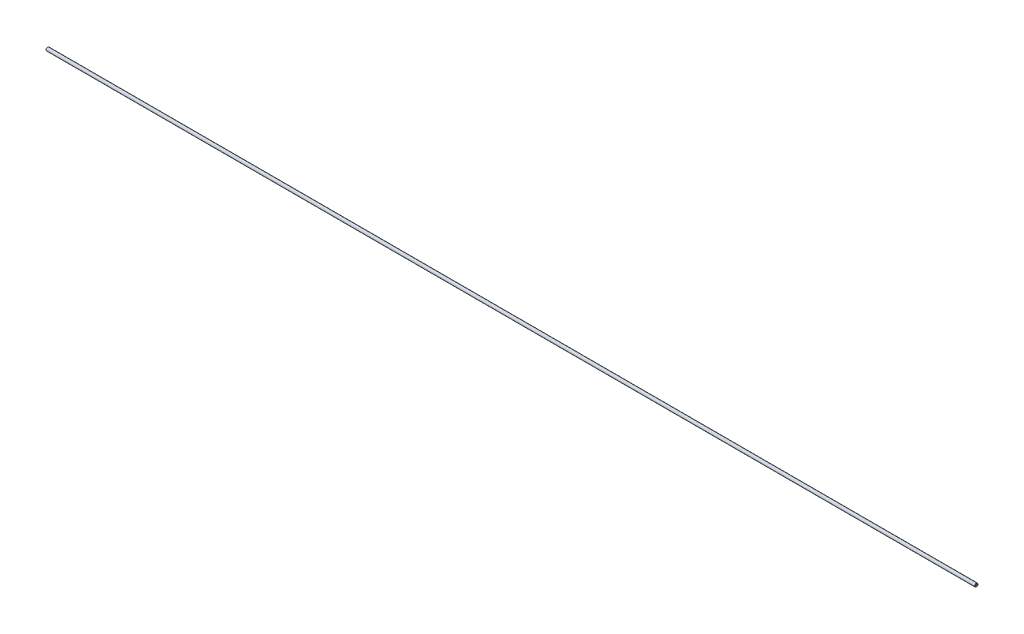
SolidWorks part; units mm, degrees
material "1060 Alloy"
ref_plane "Front Plane" through (0, 0, 0) normal (1, 0, 0) x (0, 1, 0)
ref_plane "Top Plane" through (0, 0, 0) normal (0, 0, 1) x (0, 1, 0)
ref_plane "Right Plane" through (0, 0, 0) normal (0, 1, 0) x (-1, 0, 0)
sketch "Sketch1" plane through (0, 0, 0) normal (1, 0, 0) x (0, 1, 0)
  circle A0 centre (0, 0) radius 25.4
  dimension "D1" = 50.8
extrude "Boss-Extrude1" add sketch "Sketch1" along normal blind 14373.606 contours A0
sketch "Sketch2" plane through (14373.606, 0, 0) normal (1, 0, 0) x (0, 1, 0)
  circle A0 centre (0, 0) radius 12.7
  dimension "D1" = 25.4
extrude "Cut-Extrude1" cut sketch "Sketch2" against normal through all
equation "\"D\"= 2'Diameter of the bar (in)"
equation "\"Area\"= ( \"D\" / 2 ) ^ 2 * pi'Area of the bar (in^2)"
equation "\"F\"= 500'Force (lbf)"
equation "\"del\"= .009'deflection (in)"
equation "\"E\"= 10007063.9'(psi)"
equation "\"L\"= \"del\" * \"E\" * \"Area\" / \"F\"'(in)"
